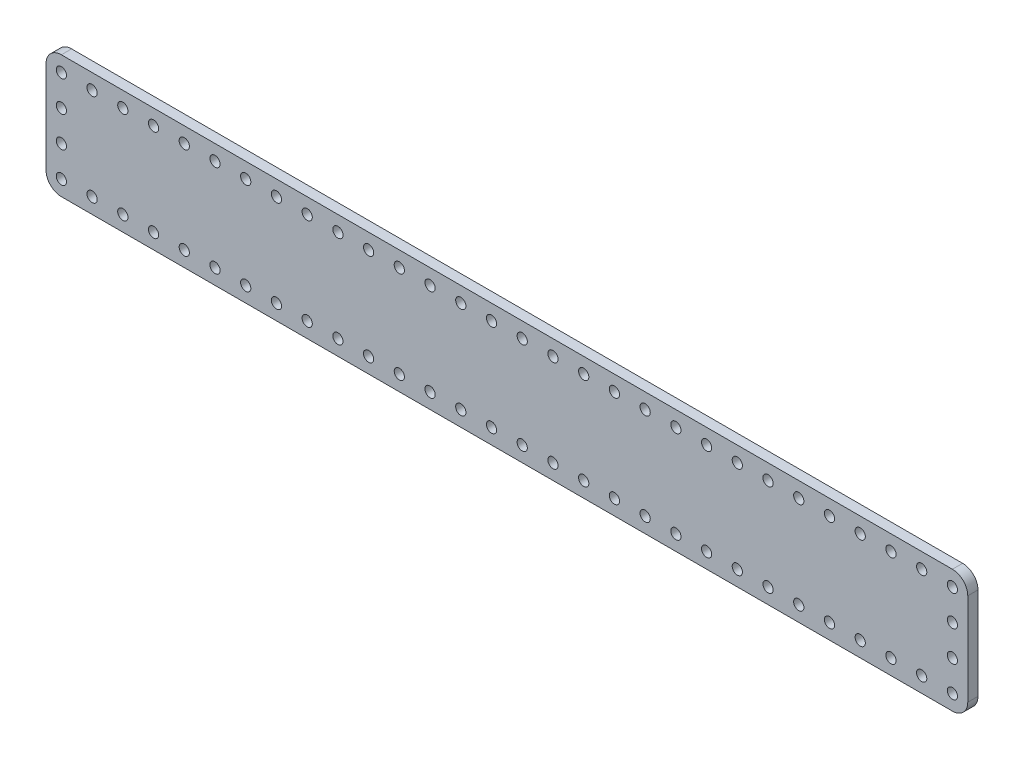
SolidWorks part; units mm, degrees
ref_plane "Alzado" through (0, 0, 0) normal (0, 0, 1) x (1, 0, 0)
ref_plane "Planta" through (0, 0, 0) normal (0, 1, 0) x (1, 0, 0)
ref_plane "Vista lateral" through (0, 0, 0) normal (1, 0, 0) x (0, 0, -1)
sketch "Model" plane through (0, 0, 0) normal (0, 0, 1) x (1, 0, 0)
  line L0 (-105.9434, 101.0565) -> (-105.9434, 74.0565)
  line L1 (-101.4434, 69.5565) -> (159.5566, 69.5565)
  line L2 (159.5566, 105.5565) -> (-101.4434, 105.5565)
  line L3 (164.0566, 74.0565) -> (164.0566, 101.0565)
  circle A0 centre (-101.4434, 101.0565) radius 1.5
  circle A1 centre (-92.4434, 101.0565) radius 1.5
  circle A2 centre (-83.4434, 101.0565) radius 1.5
  circle A3 centre (-74.4434, 101.0565) radius 1.5
  circle A4 centre (-65.4434, 101.0565) radius 1.5
  circle A5 centre (-56.4434, 101.0565) radius 1.5
  circle A6 centre (-47.4434, 101.0565) radius 1.5
  circle A7 centre (-38.4434, 101.0565) radius 1.5
  circle A8 centre (-101.4434, 92.0565) radius 1.5
  circle A9 centre (-101.4434, 83.0565) radius 1.5
  circle A10 centre (-101.4434, 74.0565) radius 1.5
  circle A11 centre (-92.4434, 74.0565) radius 1.5
  circle A12 centre (-83.4434, 74.0565) radius 1.5
  circle A13 centre (-74.4434, 74.0565) radius 1.5
  circle A14 centre (-65.4434, 74.0565) radius 1.5
  circle A15 centre (-56.4434, 74.0565) radius 1.5
  circle A16 centre (-47.4434, 74.0565) radius 1.5
  circle A17 centre (-38.4434, 74.0565) radius 1.5
  arc A18 (-101.4434, 105.5565) -> (-105.9434, 101.0565) centre (-101.4434, 101.0565) ccw
  arc A19 (-105.9434, 74.0565) -> (-101.4434, 69.5565) centre (-101.4434, 74.0565) ccw
  circle A20 centre (-29.4434, 101.0565) radius 1.5
  circle A21 centre (-29.4434, 74.0565) radius 1.5
  arc A22 (164.0566, 101.0565) -> (159.5566, 105.5565) centre (159.5566, 101.0565) ccw
  arc A23 (159.5566, 69.5565) -> (164.0566, 74.0565) centre (159.5566, 74.0565) ccw
  circle A24 centre (-20.4434, 101.0565) radius 1.5
  circle A25 centre (-20.4434, 74.0565) radius 1.5
  circle A26 centre (-11.4434, 101.0565) radius 1.5
  circle A27 centre (-2.4434, 101.0565) radius 1.5
  circle A28 centre (6.5566, 101.0565) radius 1.5
  circle A29 centre (15.5566, 101.0565) radius 1.5
  circle A30 centre (24.5566, 101.0565) radius 1.5
  circle A31 centre (33.5566, 101.0565) radius 1.5
  circle A32 centre (42.5566, 101.0565) radius 1.5
  circle A33 centre (51.5566, 101.0565) radius 1.5
  circle A34 centre (-11.4434, 74.0565) radius 1.5
  circle A35 centre (-2.4434, 74.0565) radius 1.5
  circle A36 centre (6.5566, 74.0565) radius 1.5
  circle A37 centre (15.5566, 74.0565) radius 1.5
  circle A38 centre (24.5566, 74.0565) radius 1.5
  circle A39 centre (33.5566, 74.0565) radius 1.5
  circle A40 centre (42.5566, 74.0565) radius 1.5
  circle A41 centre (51.5566, 74.0565) radius 1.5
  circle A42 centre (60.5566, 101.0565) radius 1.5
  circle A43 centre (60.5566, 74.0565) radius 1.5
  circle A44 centre (69.5566, 101.0565) radius 1.5
  circle A45 centre (69.5566, 74.0565) radius 1.5
  circle A46 centre (78.5566, 101.0565) radius 1.5
  circle A47 centre (87.5566, 101.0565) radius 1.5
  circle A48 centre (96.5566, 101.0565) radius 1.5
  circle A49 centre (105.5566, 101.0565) radius 1.5
  circle A50 centre (114.5566, 101.0565) radius 1.5
  circle A51 centre (123.5566, 101.0565) radius 1.5
  circle A52 centre (132.5566, 101.0565) radius 1.5
  circle A53 centre (141.5566, 101.0565) radius 1.5
  circle A54 centre (78.5566, 74.0565) radius 1.5
  circle A55 centre (87.5566, 74.0565) radius 1.5
  circle A56 centre (96.5566, 74.0565) radius 1.5
  circle A57 centre (105.5566, 74.0565) radius 1.5
  circle A58 centre (114.5566, 74.0565) radius 1.5
  circle A59 centre (123.5566, 74.0565) radius 1.5
  circle A60 centre (132.5566, 74.0565) radius 1.5
  circle A61 centre (141.5566, 74.0565) radius 1.5
  circle A62 centre (150.5566, 101.0565) radius 1.5
  circle A63 centre (150.5566, 74.0565) radius 1.5
  circle A64 centre (159.5566, 101.0565) radius 1.5
  circle A65 centre (159.5566, 92.0565) radius 1.5
  circle A66 centre (159.5566, 83.0565) radius 1.5
  circle A67 centre (159.5566, 74.0565) radius 1.5
extrude "Saliente-Extruir1" add sketch "Model" along normal blind 3
